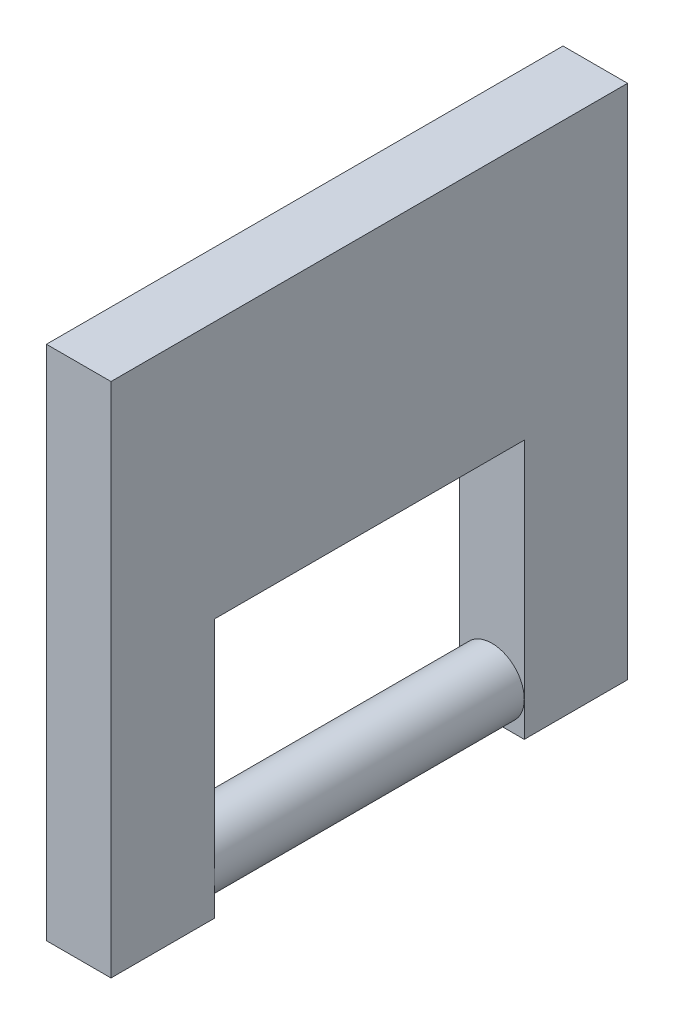
SolidWorks part; units mm, degrees
ref_plane "Front Plane" through (0, 0, 0) normal (0, 0, 1) x (1, 0, 0)
ref_plane "Top Plane" through (0, 0, 0) normal (0, 1, 0) x (1, 0, 0)
ref_plane "Right Plane" through (0, 0, 0) normal (1, 0, 0) x (0, 0, -1)
sketch "Sketch1" plane through (0, 0, 0) normal (1, 0, 0) x (0, 0, -1)
  line L1 (-66.1477, -6.3575) -> (-40.7477, -6.3575)
  line L2 (-66.1477, -6.3575) -> (-66.1477, -31.7575)
  line L3 (-66.1477, -31.7575) -> (-40.7477, -31.7575)
  line L4 (-40.7477, -6.3575) -> (-40.7477, -31.7575)
  dimension "D1" = 25.4
  dimension "D2" = 25.4
extrude "Boss-Extrude1" add sketch "Sketch1" along normal blind 3.175
sketch "Sketch2" plane through (3.175, 0, 0) normal (1, 0, 0) x (0, 0, -1)
  line L0 (-66.1477, -31.7575) -> (-40.7477, -31.7575) construction
  line L1 (-66.1477, -6.3575) -> (-66.1477, -31.7575) construction
  line L2 (-45.8277, -31.7575) -> (-61.0677, -31.7575)
  line L3 (-45.8277, -31.7575) -> (-45.8277, -19.0129)
  line L4 (-45.8277, -19.0129) -> (-61.0677, -19.0129)
  line L5 (-61.0677, -31.7575) -> (-61.0677, -19.0129)
  line L6 (-40.7477, -31.7575) -> (-40.7477, -6.3575) construction
  dimension "D1" = 5.08
  dimension "D2" = 5.08
extrude "Cut-Extrude1" cut sketch "Sketch2" against normal through all
sketch "Sketch3" plane through (0, 0, 45.8277) normal (0, 0, 1) x (1, 0, 0)
  line L0 (0, -31.7575) -> (0, -19.0129) construction
  circle A0 centre (1.5875, -30.0449) radius 1.5875
  dimension "D1" = 1.5875
  dimension "D2" = 3.175
extrude "Boss-Extrude4" add sketch "Sketch3" along normal blind 15.24
